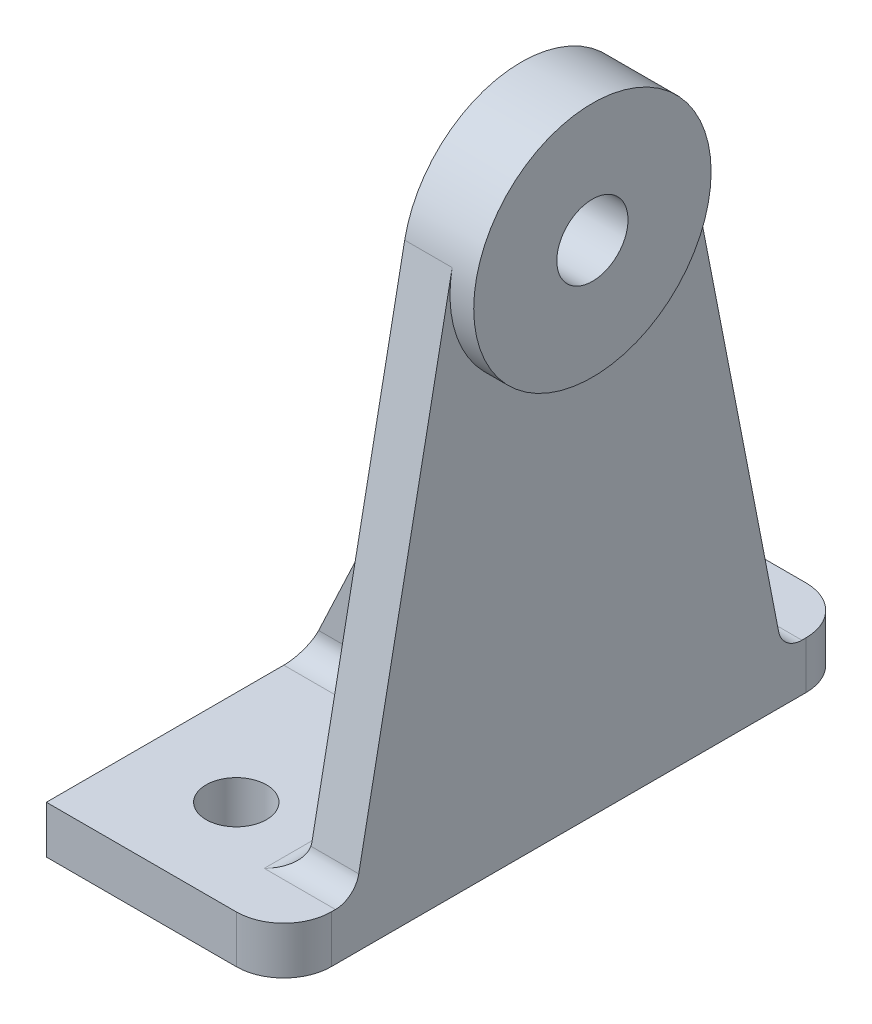
SolidWorks part; units mm, degrees
ref_plane "Front Plane" through (0, 0, 0) normal (0, 0, 1) x (1, 0, 0)
ref_plane "Top Plane" through (0, 0, 0) normal (0, 1, 0) x (1, 0, 0)
ref_plane "Right Plane" through (0, 0, 0) normal (1, 0, 0) x (0, 0, -1)
sketch "Sketch2" plane through (0, 0, 0) normal (0, 1, 0) x (1, 0, 0)
  line L0 (0, 0) -> (31.75, 0)
  line L1 (31.75, 0) -> (31.75, 76.2)
  line L2 (31.75, 76.2) -> (0, 76.2)
  line L3 (0, 76.2) -> (0, 0)
  line L4 (0, 38.1) -> (31.75, 38.1) construction
  circle A0 centre (12.7, 12.7) radius 4.0386
  circle A1 centre (12.7, 63.5) radius 4.0386
  dimension "D3" = 12.7
  dimension "D1" = 12.7
  dimension "D2" = 76.2
extrude "Extrude1" add sketch "Sketch2" against normal blind 6.35
ref_plane "Plane1" through (31.75, 0, 0) normal (1, 0, 0) x (0, 0, -1)
sketch "Sketch3" plane through (31.75, 0, 0) normal (1, 0, 0) x (0, 0, -1)
  line L0 (0, 0) -> (76.2, 0) construction
  line L1 (9.525, 0) -> (66.675, 0)
  line L2 (38.1, 0) -> (38.1, 63.5) construction
  line L3 (0, 0) -> (0, 13.7084) construction
  line L4 (9.525, 0) -> (9.525, 13.7084) construction
  line L5 (9.525, 0) -> (22.5193, 66.5426)
  line L6 (66.675, 0) -> (53.6807, 66.5426)
  arc A0 (53.6807, 66.5426) -> (22.5193, 66.5426) centre (38.1, 63.5) ccw
  dimension "D1" = 9.525
extrude "Extrude2" add sketch "Sketch3" against normal blind 6.35
sketch "Sketch4" plane through (31.75, 0, 0) normal (1, 0, 0) x (0, 0, -1)
  circle A0 centre (38.1, 63.5) radius 15.875
extrude "Extrude3" add sketch "Sketch4" along normal blind 3.175
ref_plane "Plane2" through (25.4, 0, -9.525) normal (-1, 0, 0) x (0, 0, 1)
sketch "Sketch5" plane through (25.4, 0, -9.525) normal (-1, 0, 0) x (0, 0, 1)
  line L0 (0, 0) -> (-57.15, 0) construction
  line L1 (0, 0) -> (-57.15, 0)
  line L2 (-28.575, 0) -> (-28.575, 54.102) construction
  dimension "D1" = 54.102
ref_plane "Plane3" through (0, 0, 0) normal (-0.9052, 0.425, 0) x (0, 0, 1)
sketch "Sketch6" plane through (0, 0, 0) normal (-0.9052, 0.425, 0) x (0, 0, 1)
  line L0 (-38.1, 59.7678) -> (-38.1, 0)
  line L1 (-76.2, 0) -> (0, 0) construction
rib "Rib1" sketch "Sketch6" sketch "Sketch6" thickness 6.35 extrusion direction normal to sketch draft on no parameters "D1"=6.35
sketch "Sketch7" plane through (25.4, 0, -9.525) normal (-1, 0, 0) x (0, 0, 1)
  circle A0 centre (-28.575, 63.5) radius 4.7625
extrude "Extrude4" cut sketch "Sketch7" against normal through all
fillet "Fillet1" radius 3.175 8 edges at (25.4, 0, -22.225) (25.4, 27.051, -34.925) (12.7, 0, -34.925) (25.4, 27.051, -41.275) (12.7, 0, -41.275) (25.4, 0, -53.975)
fillet "Fillet2" radius 6.35 2 edges at (31.75, -3.175, -76.2) (31.75, -3.175, 0)
